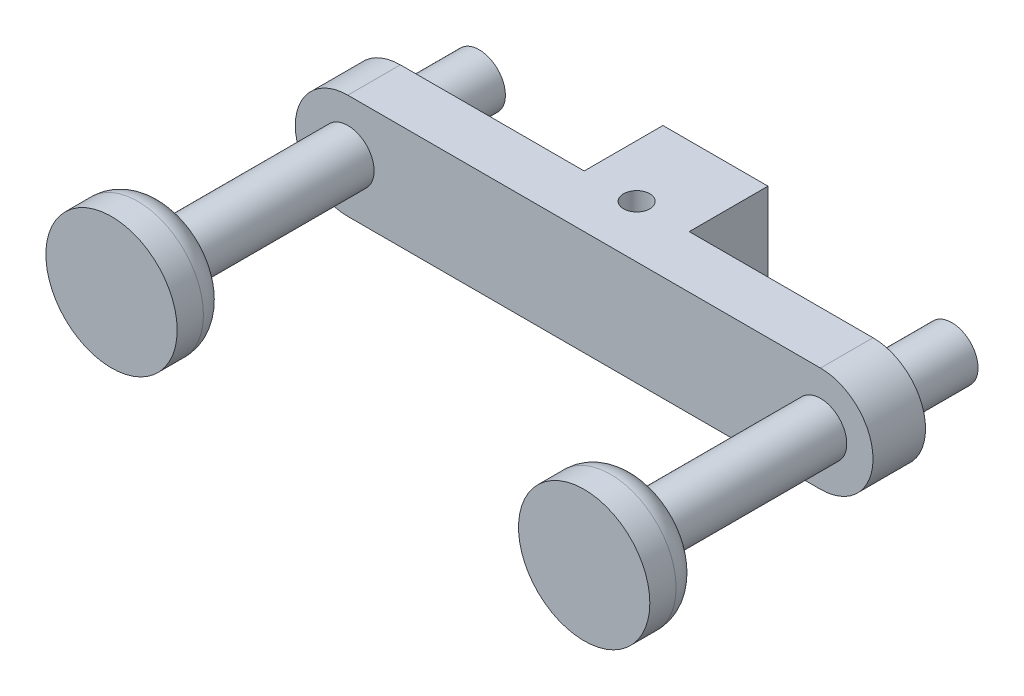
SolidWorks part; units mm, degrees
ref_plane "Front Plane" through (0, 0, 0) normal (0, 0, 1) x (1, 0, 0)
ref_plane "Top Plane" through (0, 0, 0) normal (0, 1, 0) x (1, 0, 0)
ref_plane "Right Plane" through (0, 0, 0) normal (1, 0, 0) x (0, 0, -1)
sketch "Sketch1" plane through (0, 0, 0) normal (0, 0, 1) x (1, 0, 0)
  line L0 (-114.3, 0) -> (114.3, 0) construction
  line L1 (-114.3, 25.4) -> (114.3, 25.4)
  line L2 (114.3, -25.4) -> (-114.3, -25.4)
  circle A0 centre (-114.3, 0) radius 12.7
  circle A1 centre (114.3, 0) radius 12.7
  arc A2 (-114.3, 25.4) -> (-114.3, -25.4) centre (-114.3, 0) ccw
  arc A3 (114.3, -25.4) -> (114.3, 25.4) centre (114.3, 0) ccw
  point P4 (0, 0)
  dimension "D2" = 25.4
  dimension "D3" = 25.4
  dimension "D4" = 50.8
  dimension "D5" = 50.8
  dimension "D1" = 228.6
extrude "Boss-Extrude1" add sketch "Sketch1" along normal blind 25.4
sketch "Sketch2" plane through (0, 0, 0) normal (0, 1, 0) x (1, 0, 0)
  line L0 (0, 61.1357) -> (0, -57.6399) construction
  line L1 (114.3, 0) -> (-114.3, 0) construction
  line L2 (25.4, 38.1) -> (-25.4, 38.1)
  line L3 (25.4, 38.1) -> (25.4, 0)
  line L4 (25.4, 0) -> (-25.4, 0)
  line L5 (-25.4, 38.1) -> (-25.4, 0)
  line L6 (25.4, 38.1) -> (-25.4, 0) construction
  line L7 (25.4, 0) -> (-25.4, 38.1) construction
  point P3 (0, 19.05)
  dimension "D1" = 50.8
  dimension "D2" = 38.1
extrude "Boss-Extrude2" add sketch "Sketch2" along normal up to vertex (25.4 mm away) and the other way up to vertex (25.4 mm away)
sketch "Sketch3" plane through (0, 25.4, 0) normal (0, 1, 0) x (1, 0, 0)
  circle A0 centre (0, 0) radius 6.35
  dimension "D1" = 12.7
extrude "Cut-Extrude1" cut sketch "Sketch3" against normal through all
sketch "Sketch4" plane through (0, 0, -38.1) normal (0, 0, -1) x (-1, 0, 0)
  circle A0 centre (0, 0) radius 12.7
  dimension "D1" = 25.4
extrude "Cut-Extrude2" cut sketch "Sketch4" against normal blind 12.7
ref_plane "Plane1" through (0, 0, -38.1) normal (0, 0, -1) x (-1, 0, 0)
sketch "Sketch5" plane through (0, 0, -38.1) normal (0, 0, -1) x (-1, 0, 0)
  circle A0 centre (114.3, 0) radius 12.7 construction
  circle A1 centre (-114.3, 0) radius 12.7 construction
  circle A2 centre (114.3, 0) radius 12.7
  circle A3 centre (-114.3, 0) radius 12.7
extrude "Boss-Extrude3" add sketch "Sketch5" against normal blind 152.4
ref_plane "Plane2" through (0, 0, 114.3) normal (0, 0, 1) x (1, 0, 0)
sketch "Sketch6" plane through (0, 0, 114.3) normal (0, 0, 1) x (1, 0, 0)
  circle A0 centre (-114.3, 0) radius 31.75
  circle A1 centre (114.3, 0) radius 31.75
  dimension "D1" = 63.5
  dimension "D2" = 63.5
extrude "Boss-Extrude4" add sketch "Sketch6" along normal blind 25.4
fillet "Fillet1" radius 12.7 2 edges at (146.05, 0, 114.3) (-82.55, 0, 114.3)
